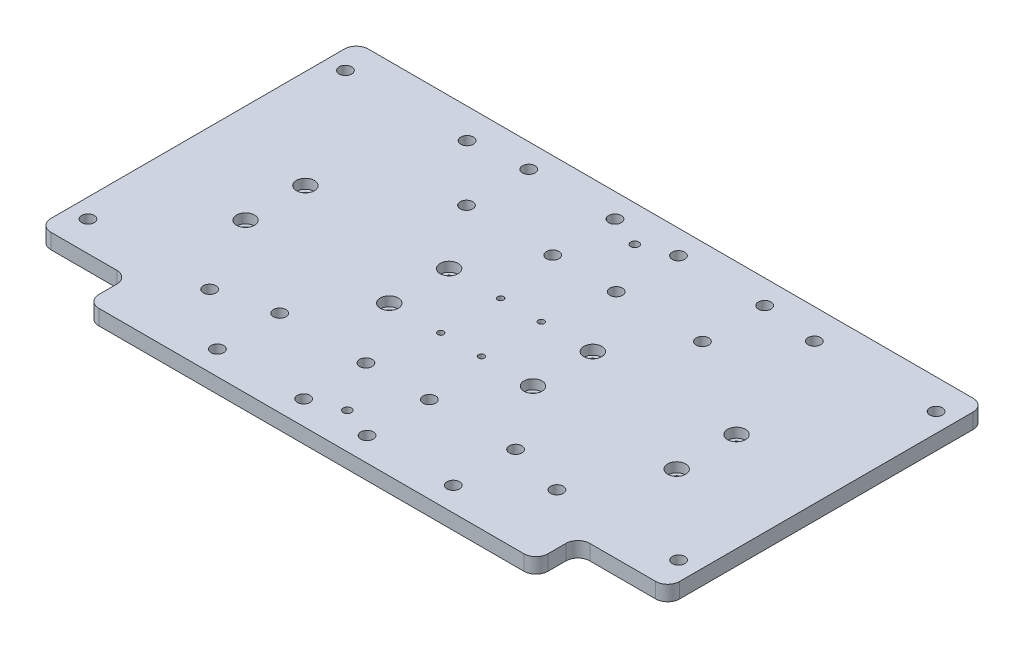
SolidWorks part; units mm, degrees
material "Plain Carbon Steel"
ref_plane "Front Plane" through (0, 0, 0) normal (0, 0, 1) x (1, 0, 0)
ref_plane "Top Plane" through (0, 0, 0) normal (0, 1, 0) x (1, 0, 0)
ref_plane "Right Plane" through (0, 0, 0) normal (1, 0, 0) x (0, 0, -1)
sketch "Sketch1" plane through (0, 0, 0) normal (0, 1, 0) x (1, 0, 0)
  line L0 (-252.5, -115) -> (-197.5, -115)
  line L1 (177.5, -150) -> (-177.5, -150)
  line L2 (262.5, -105) -> (262.5, 140)
  line L3 (252.5, 150) -> (-252.5, 150)
  line L4 (-262.5, -105) -> (-262.5, 140)
  line L5 (262.5, -150) -> (-262.5, 150) construction
  line L6 (262.5, 150) -> (-262.5, -150) construction
  line L7 (-187.5, -125) -> (-187.5, -140)
  line L8 (187.5, -140) -> (187.5, -125)
  line L9 (197.5, -115) -> (252.5, -115)
  arc A0 (-252.5, 150) -> (-262.5, 140) centre (-252.5, 140) ccw
  arc A1 (262.5, 140) -> (252.5, 150) centre (252.5, 140) ccw
  arc A2 (262.5, -105) -> (252.5, -115) centre (252.5, -105) cw
  arc A3 (187.5, -125) -> (197.5, -115) centre (197.5, -125) cw
  arc A4 (177.5, -150) -> (187.5, -140) centre (177.5, -140) ccw
  arc A5 (-177.5, -150) -> (-187.5, -140) centre (-177.5, -140) cw
  arc A6 (-197.5, -115) -> (-187.5, -125) centre (-197.5, -125) cw
  arc A7 (-262.5, -105) -> (-252.5, -115) centre (-252.5, -105) ccw
  point P0 (0, 0)
  point P18 (262.5, 150)
  point P21 (262.5, -115)
  point P26 (187.5, -150)
  point P29 (-187.5, -150)
  dimension "D3" = 375
  dimension "D5" = 10
  dimension "D1" = 525
  dimension "D2" = 300
  dimension "D4" = 265
extrude "Boss-Extrude1" add sketch "Sketch1" along normal mid plane 12.7
hole_wizard "M10 Clearance Hole1" positions "Sketch3" profile "Sketch2" hole size "M10" standard "ANSI Metric" end condition through all
sketch "Sketch3" plane through (0, 6.35, 0) normal (0, 1, 0) x (1, 0, 0)
  line L0 (0, 0) -> (-262.5, 0) construction
  line L4 (0, 0) -> (0, 150) construction
  line L5 (252.5, 150) -> (-252.5, 150) construction
  line L8 (-177.5, -150) -> (177.5, -150) construction
  line L9 (-246.6, 125) -> (-246.6, -90) construction
  line L10 (-262.5, 140) -> (-262.5, -105) construction
  point P0 (-98.5, -130)
  point P2 (-26.5, -130)
  point P4 (-26.5, -78)
  point P6 (-98.5, -78)
  point P32 (98.5, -78)
  point P33 (26.5, -78)
  point P34 (26.5, -130)
  point P35 (98.5, -130)
  point P38 (98.5, 130)
  point P39 (26.5, 130)
  point P40 (26.5, 78)
  point P41 (98.5, 78)
  point P42 (-98.5, 78)
  point P43 (-26.5, 78)
  point P44 (-26.5, 130)
  point P45 (-98.5, 130)
  point P46 (-246.6, 125)
  point P48 (-145, 125)
  point P50 (-145, -90)
  point P52 (-246.6, -90)
  point P59 (145, -90)
  point P60 (246.6, -90)
  point P61 (145, 125)
  point P62 (246.6, 125)
  dimension "D1" = 52
  dimension "D2" = 72
  dimension "D3" = 125
  dimension "D4" = 20
  dimension "D5" = 215
  dimension "D6" = 101.6
  dimension "D7" = 145
  dimension "D8" = 125
sketch "Sketch2" plane through (-98.5, 6.35, 130) normal (1, 0, 0) x (0, 0, 1)
  line L0 (0, 0) -> (0, 12.7)
  line L1 (0, 12.7) -> (5.25, 12.7)
  line L2 (5.25, 12.7) -> (5.25, 0)
  line L5 (5.25, 0) -> (0, 0)
  line L11 (0, -6.35) -> (0, 107.95) construction
  dimension "Thru Hole Dia." = 10.5
  dimension "Thru Hole Depth" = 12.7
hole_wizard "CBORE for M8 SHCS1" positions "Sketch5" profile "Sketch4" counterbore size "M8" standard "ANSI Metric" end condition through all
sketch "Sketch5" plane through (0, 6.35, 0) normal (0, 1, 0) x (1, 0, 0)
  line L0 (60, 25) -> (60, -25) construction
  line L2 (0, 0) -> (60, 0) construction
  point P0 (60, 25)
  point P2 (60, -25)
  dimension "D1" = 50
  dimension "D2" = 60
sketch "Sketch4" plane through (60, 6.35, -25) normal (1, 0, 0) x (0, 0, 1)
  line L0 (0, 0) -> (0, 12.7)
  line L1 (0, 12.7) -> (4.5, 12.7)
  line L3 (4.5, 12.7) -> (4.5, 8)
  line L4 (4.5, 8) -> (7.5, 8)
  line L5 (7.5, 8) -> (7.5, 0)
  line L7 (7.5, 0) -> (0, 0)
  line L11 (0, -6.35) -> (0, 107.95) construction
  dimension "Thru Hole Dia." = 9
  dimension "Thru Hole Depth" = 12.7
  dimension "C'Bore Dia." = 15
  dimension "C'Bore Depth" = 8
pattern_linear "LPattern1" count 2 spacing 120 along (1, 0, 0) count 3 spacing 120 along (-1, 0, 0) of "CBORE for M8 SHCS1"
hole_wizard "M6x1.0 Tapped Hole1" positions "Sketch7" profile "Sketch6" tap size "M6x1.0" standard "JIS" end condition through all
sketch "Sketch7" plane through (0, 6.35, 0) normal (0, 1, 0) x (1, 0, 0)
  line L0 (17, 25) -> (17, -25) construction
  line L2 (17, 0) -> (-17, 0) construction
  point P0 (17, 25)
  point P2 (17, -25)
  point P15 (-17, -25)
  point P17 (-17, 25)
  dimension "D1" = 50
  dimension "D2" = 34
sketch "Sketch6" plane through (17, 6.35, -25) normal (1, 0, 0) x (0, 0, 1)
  line L0 (0, 0) -> (0, 12.7)
  line L1 (0, 12.7) -> (2.5, 12.7)
  line L2 (2.5, 12.7) -> (2.5, 0)
  line L5 (2.5, 0) -> (0, 0)
  line L11 (0, -6.35) -> (0, 107.95) construction
  dimension "Thru Tap Drill Dia." = 5
  dimension "Thru Tap Drill Depth" = 12.7
cosmetic thread "Hole Thread1"
cosmetic thread "Hole Thread2"
cosmetic thread "Hole Thread3"
cosmetic thread "Hole Thread4"
hole_wizard "M8x1.25 Tapped Hole1" positions "Sketch9" profile "Sketch8" tap size "M8x1.25" standard "ANSI Metric" end condition through all
sketch "Sketch9" plane through (0, 6.35, 0) normal (0, 1, 0) x (1, 0, 0)
  line L0 (0, 120) -> (0, -120) construction
  line L2 (-177.5, -150) -> (177.5, -150) construction
  point P0 (0, -120)
  point P2 (0, 120)
  dimension "D1" = 30
sketch "Sketch8" plane through (0, 6.35, 120) normal (1, 0, 0) x (0, 0, 1)
  line L0 (0, 0) -> (0, 12.7)
  line L1 (0, 12.7) -> (3.4, 12.7)
  line L2 (3.4, 12.7) -> (3.4, 0)
  line L5 (3.4, 0) -> (0, 0)
  line L11 (0, -6.35) -> (0, 107.95) construction
  dimension "Thru Tap Drill Dia." = 6.8
  dimension "Thru Tap Drill Depth" = 12.7
cosmetic thread "Hole Thread5"
cosmetic thread "Hole Thread6"
